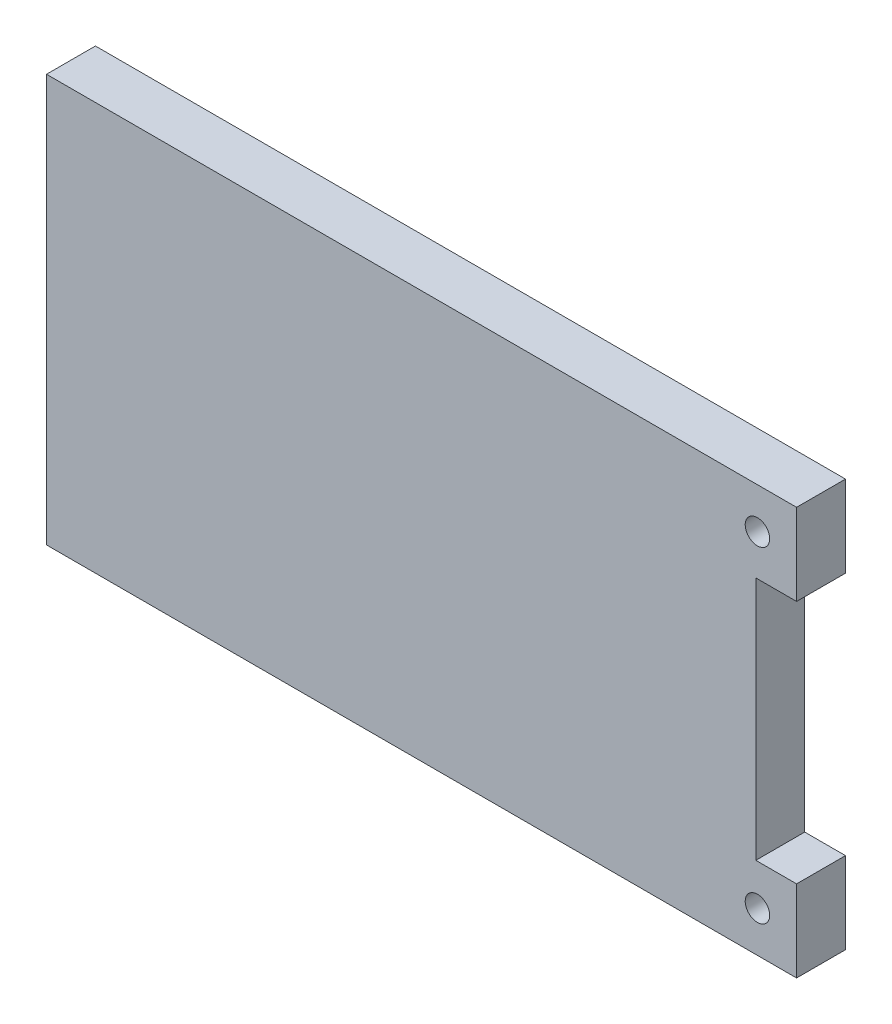
SolidWorks part; units mm, degrees
ref_plane "Front Plane" through (0, 0, 0) normal (0, 0, 1) x (1, 0, 0)
ref_plane "Top Plane" through (0, 0, 0) normal (0, 1, 0) x (1, 0, 0)
ref_plane "Right Plane" through (0, 0, 0) normal (1, 0, 0) x (0, 0, -1)
sketch "Sketch1" plane through (0, 0, 0) normal (0, 0, 1) x (1, 0, 0)
  line L11 (148.35, 52.1) -> (148.35, 51.1)
  line L12 (148.35, 51.1) -> (147.85, 51.1)
  line L13 (147.85, 51.1) -> (147.85, 48.1)
  line L14 (147.85, 48.1) -> (148.35, 48.1)
  line L15 (148.35, 48.1) -> (148.35, 47.1)
  line L16 (148.35, 47.1) -> (146.55, 47.1)
  line L17 (146.05, 47.1) -> (140.55, 47.1)
  line L18 (139.15, 47.1) -> (140.05, 47.1)
  line L19 (139.15, 48.3) -> (139.15, 47.1)
  line L20 (139.15, 49.3) -> (139.15, 52.1)
  line L21 (139.15, 52.1) -> (148.35, 52.1)
  line L22 (139.15, 49.3) -> (139.15, 48.3)
  line L23 (140.05, 47.1) -> (140.55, 47.1)
  line L24 (146.05, 47.1) -> (146.55, 47.1)
  circle A2 centre (147.87, 47.6) radius 0.15
  circle A3 centre (147.87, 51.6) radius 0.15
extrude "Boss-Extrude1" add sketch "Sketch1" along normal blind 0.6
